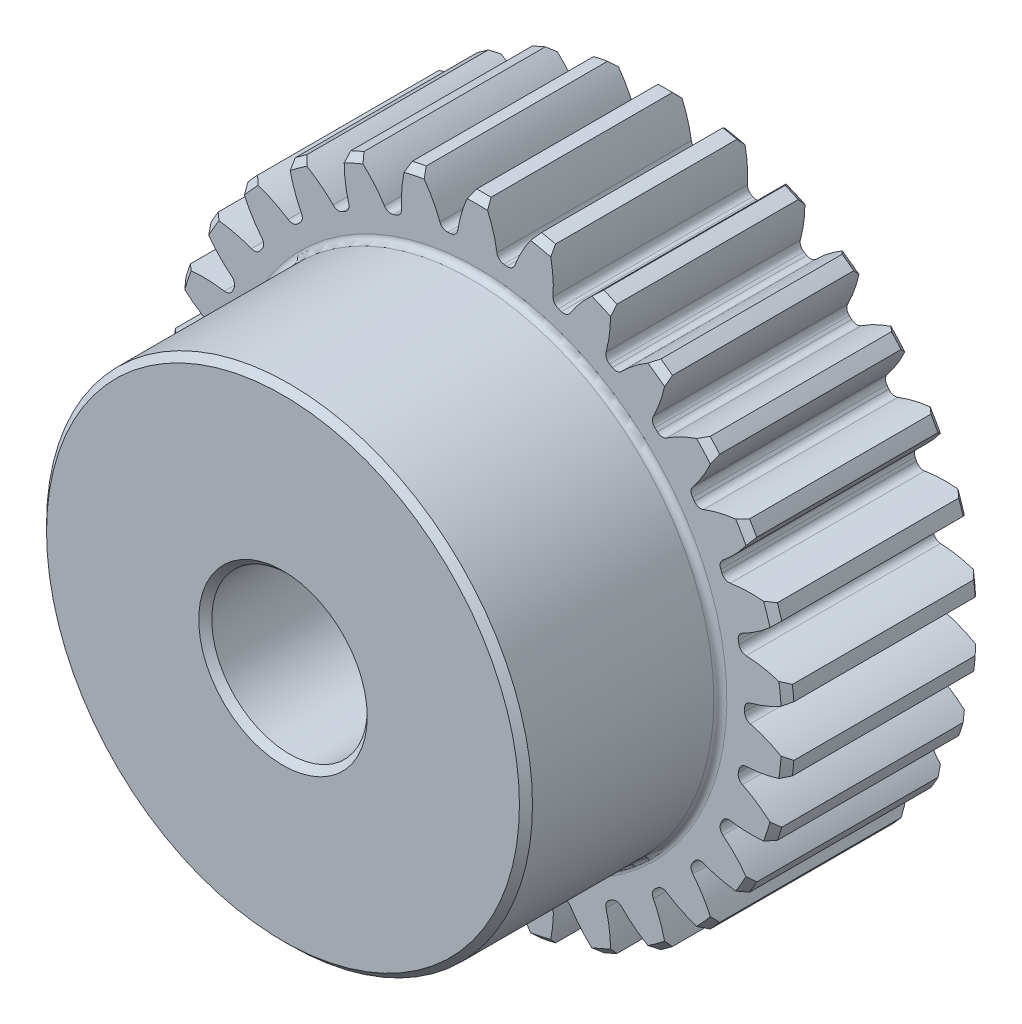
SolidWorks part; units mm, degrees
ref_plane "Front Plane" through (0, 0, 0) normal (0, 0, 1) x (1, 0, 0)
ref_plane "Top Plane" through (0, 0, 0) normal (0, 1, 0) x (1, 0, 0)
ref_plane "Right Plane" through (0, 0, 0) normal (1, 0, 0) x (0, 0, -1)
sketch "Sketch1" plane through (0, 0, 0) normal (0, 0, 1) x (1, 0, 0)
  line L0 (0, 0) -> (0, 15) construction
  line L1 (-4.8209, 16.7547) -> (4.8209, 13.2453) construction
  circle A0 centre (0, 0) radius 13.75 construction
  circle A1 centre (0, 0) radius 16 construction
  circle A2 centre (0, 0) radius 15 construction
  circle A3 centre (0, 0) radius 14.0954 construction
  circle A4 centre (0, 0) radius 12.5 construction
  circle A5 centre (0, 0) radius 4 construction
  point P8 (0.5, 0)
  point P13 (15, 0)
  dimension "OD" = 32
  dimension "Root Diameter" = 27.5
  dimension "Gear Pitch Diameter" = 30
  dimension "Base Diameter" = 28.1908
  dimension "Hub Diameter" = 25
  dimension "For Shaft Diameter" = 8
  dimension "Pressure Angle" = 20
  dimension "Number of Teeth" = 30
  dimension "Module" = 1
sketch "Sketch2" plane through (0, 0, 0) normal (1, 0, 0) x (0, 0, -1)
  line L0 (-10, 0) -> (10, 0) construction
  line L1 (10, 16) -> (10, -16) construction
  line L2 (0, -12.5) -> (-10, -12.5) construction
  line L3 (-10, 16) -> (10, 16) construction
  line L8 (-10, -12.5) -> (-10, 12.5) construction
  point P4 (0, 16)
  point P5 (-5, 0)
  dimension "Overall Width" = 20
  dimension "Hub Width" = 10
  dimension "Approx Set Screw Positon" = 5
  dimension "Face Width" = 10
sketch "Sketch3" plane through (0, 0, 0) normal (0, 0, 1) x (1, 0, 0)
  circle A0 centre (0, 0) radius 16
  circle A1 centre (0, 0) radius 16 construction
extrude "Boss-Extrude1" add sketch "Sketch3" against normal up to vertex (10 mm away) and the other way up to vertex (10 mm away) up to point (0, 0, -10) other way up to point (0, 0, 10)
sketch "Sketch5" plane through (0, 0, 0) normal (1, 0, 0) x (0, 0, -1)
  line L1 (0, 12.5) -> (-10, 12.5)
  line L2 (0, 12.5) -> (0, 16)
  line L3 (0, 16) -> (-10, 16)
  line L4 (-10, 12.5) -> (-10, 16)
  line L5 (-10, 0) -> (10, 0)
  line L6 (-10, 0) -> (-10, 4)
  line L7 (-10, 4) -> (10, 4)
  line L8 (10, 0) -> (10, 4)
  point P5 (0, 12.5)
  point P12 (0, 4)
revolve "Cut-Revolve1" cut sketch "Sketch5" angle 360 about L0
fillet "Fillet2" radius 0.3355 1 edges at (0, -12.5, 0)
chamfer "Chamfer1" distance 0.3355 angle 45 5 edges at (0, -4, -10) (0, -16, 0) (16, 0, -10) (0, -4, 10) (0, -12.5, 10)
sketch "Sketch4" plane through (0, 0, 0) normal (0, 0, 1) x (1, 0, 0)
  line L0 (13.7444, 0.3927) -> (13.7444, -0.3927)
  arc A3 (15.9467, 1.3054) -> (15.9467, -1.3054) centre (0, 0) cw
  circle A4 centre (0, 0) radius 16 construction
  arc A5 (13.7444, 0.3927) -> (15.9467, 1.3054) centre (12.3619, 6.8422) ccw
  circle A8 centre (0, 0) radius 13.75 construction
  arc A9 (13.7444, -0.3927) -> (15.9467, -1.3054) centre (12.3619, -6.8422) cw
  spline S0 degree 4 poles (14.0855, 0.5278) (14.0885, 0.528) (14.0969, 0.5285) (14.1128, 0.5299) (14.1387, 0.5328) (14.1717, 0.5373) (14.2142, 0.5441) (14.2642, 0.5535) (14.319, 0.5651) (14.3785, 0.5792) (14.4378, 0.5946) (14.4967, 0.6111) (14.5554, 0.6286) (14.6262, 0.6511) (14.7109, 0.6798) (14.8096, 0.716) (14.9211, 0.76) (15.0342, 0.8081) (15.1451, 0.8581) (15.2566, 0.9116) (15.3642, 0.9655) (15.4753, 1.0247) (15.5776, 1.0809) (15.6916, 1.1472) (15.7833, 1.2018) (15.9036, 1.2774) (15.9744, 1.3231) (16.0571, 1.3779) (16.0936, 1.4029) (16.1161, 1.4183) knots 0 0 0 0 0 0.005377 0.015084 0.028532 0.04661 0.064855 0.092111 0.119476 0.146842 0.174209 0.201575 0.228941 0.256307 0.307035 0.361767 0.4165 0.471232 0.525964 0.580697 0.635429 0.690161 0.744894 0.799626 0.854358 0.909091 0.954545 1 1 1 1 1 construction
  spline S1 degree 4 poles (14.0855, 0.5278) (14.0885, 0.528) (14.0969, 0.5285) (14.1128, 0.5299) (14.1387, 0.5328) (14.1717, 0.5373) (14.2142, 0.5441) (14.2642, 0.5535) (14.319, 0.5651) (14.3785, 0.5792) (14.4378, 0.5946) (14.4967, 0.6111) (14.5554, 0.6286) (14.6262, 0.6511) (14.7109, 0.6798) (14.8096, 0.716) (14.9211, 0.76) (15.0342, 0.8081) (15.1451, 0.8581) (15.2566, 0.9116) (15.3642, 0.9655) (15.4753, 1.0247) (15.5776, 1.0809) (15.6916, 1.1472) (15.7833, 1.2018) (15.8775, 1.261) (15.9233, 1.2902) (15.9467, 1.3054) knots 0 0 0 0 0 0.005377 0.015084 0.028532 0.04661 0.064855 0.092111 0.119476 0.146842 0.174209 0.201575 0.228941 0.256307 0.307035 0.361767 0.4165 0.471232 0.525964 0.580697 0.635429 0.690161 0.744894 0.799626 0.854358 0.909091 0.909091 0.909091 0.909091 0.909091 construction
  spline S2 degree 4 poles (14.0855, -0.5278) (14.0885, -0.528) (14.0969, -0.5285) (14.1128, -0.5299) (14.1387, -0.5328) (14.1717, -0.5373) (14.2142, -0.5441) (14.2642, -0.5535) (14.319, -0.5651) (14.3785, -0.5792) (14.4378, -0.5946) (14.4967, -0.6111) (14.5554, -0.6286) (14.6262, -0.6511) (14.7109, -0.6798) (14.8096, -0.716) (14.9211, -0.76) (15.0342, -0.8081) (15.1451, -0.8581) (15.2566, -0.9116) (15.3642, -0.9655) (15.4753, -1.0247) (15.5776, -1.0809) (15.6916, -1.1472) (15.7833, -1.2018) (15.9036, -1.2774) (15.9744, -1.3231) (16.0571, -1.3779) (16.0936, -1.4029) (16.1161, -1.4183) knots 0 0 0 0 0 0.005377 0.015084 0.028532 0.04661 0.064855 0.092111 0.119476 0.146842 0.174209 0.201575 0.228941 0.256307 0.307035 0.361767 0.4165 0.471232 0.525964 0.580697 0.635429 0.690161 0.744894 0.799626 0.854358 0.909091 0.954545 1 1 1 1 1 construction
  spline S3 degree 4 poles (14.0855, -0.5278) (14.0885, -0.528) (14.0969, -0.5285) (14.1128, -0.5299) (14.1387, -0.5328) (14.1717, -0.5373) (14.2142, -0.5441) (14.2642, -0.5535) (14.319, -0.5651) (14.3785, -0.5792) (14.4378, -0.5946) (14.4967, -0.6111) (14.5554, -0.6286) (14.6262, -0.6511) (14.7109, -0.6798) (14.8096, -0.716) (14.9211, -0.76) (15.0342, -0.8081) (15.1451, -0.8581) (15.2566, -0.9116) (15.3642, -0.9655) (15.4753, -1.0247) (15.5776, -1.0809) (15.6916, -1.1472) (15.7833, -1.2018) (15.8775, -1.261) (15.9233, -1.2902) (15.9467, -1.3054) knots 0 0 0 0 0 0.005377 0.015084 0.028532 0.04661 0.064855 0.092111 0.119476 0.146842 0.174209 0.201575 0.228941 0.256307 0.307035 0.361767 0.4165 0.471232 0.525964 0.580697 0.635429 0.690161 0.744894 0.799626 0.854358 0.909091 0.909091 0.909091 0.909091 0.909091 construction
  dimension "D1" = 0.7854
extrude "Cut-Extrude1" cut sketch "Sketch4" against normal through all both and the other way through all
fillet "Fillet1" radius 0.3927 2 edges at (13.7444, 0.3927, -5) (13.7444, -0.3927, -5)
pattern_circular "CirPattern1" count 30 over 360 about axis through (0, 0, 0) along (0, 0, 1) of "Cut-Extrude1", "Fillet1"
equation "\"Number of Teeth\"= 30"
equation "\"Module\"= 1"
equation "\"Diametral Pitch\"= 1 / \"Module\""
equation "\"Dedendum\"= 1.25 / \"Diametral Pitch\""
equation "\"Pitch Diameter\"= \"Module\" * \"Number of Teeth\""
equation "\"Root Diameter\"= \"Pitch Diameter\" - ( 2 * \"Dedendum\" )"
equation "\"Root Diameter@Sketch1\"=\"Root Diameter\""
equation "\"OD@Sketch1\" = \"Outside Diameter\""
equation "\"D1@CirPattern1\"=\"Number of Teeth\""
equation "\"Pressure Angle\"=20"
equation "\"Base Diameter\"= \"Pitch Diameter\" * cos ( \"Pressure Angle\" )"
equation "\"Outside Diameter\"= ( \"Number of Teeth\" + 2 ) / \"Diametral Pitch\""
equation "\"Pitch Angle\"= 360deg / \"Number of Teeth\""
equation "\"Alpha\"= sqr ( \"Pitch Diameter\" ^ 2 - \"Base Diameter\" ^ 2 ) / \"Base Diameter\" * 180 / PI - \"Pressure Angle\""
equation "\"Beta\"= ( \"Pitch Angle\" / 4 - \"Alpha\" )"
equation "\"Phi\"= sqr ( ( \"Outside Diameter\" / 2 ) ^ 2 - ( \"Base Diameter\" / 2 ) ^ 2 ) / ( \"Base Diameter\" / 2 )"
equation "\"Addendum\"= 1 / \"Diametral Pitch\""
equation "\"WorkingDepth\"= 2 / \"Diametral Pitch\""
equation "\"WholeDepth\"= 2.25 / \"Diametral Pitch\""
equation "\"Clearance\"= 0.25 / \"Diametral Pitch\""
equation "\"ToothThickness\"= ( pi * 2 ) / \"Diametral Pitch\""
equation "\"CircularPitch\"= pi / \"Diametral Pitch\""
equation "\"Number of Teeth@Sketch1\"=\"Number of Teeth\""
equation "\"Module@Sketch1\"=\"Module\""
equation "\"Pressure Angle@Sketch1\"=\"Pressure Angle\""
equation "\"Gear Pitch Diameter@Sketch1\"=\"Pitch Diameter\""
equation "\"Base Diameter@Sketch1\"=\"Base Diameter\""
equation "\"Fillet\"= \"Clearance\" * cos ( \"Pressure Angle\" ) * tan ( ( 90 + \"Pressure Angle\" ) / 2 )"
equation "\"D1@Fillet2\"=\"Fillet\""
equation "\"Approx Set Screw Positon@Sketch2\" = \"Hub Width@Sketch2\" / 2"
equation "\"D2\"= \"Fillet\" * 2"
equation "\"D1@Chamfer1\"=\"Fillet\""
equation "\"D1@Sketch4\"=\"CircularPitch\"*0.25"
equation "\"D1@Fillet1\"=\"CircularPitch\"*0.125"
